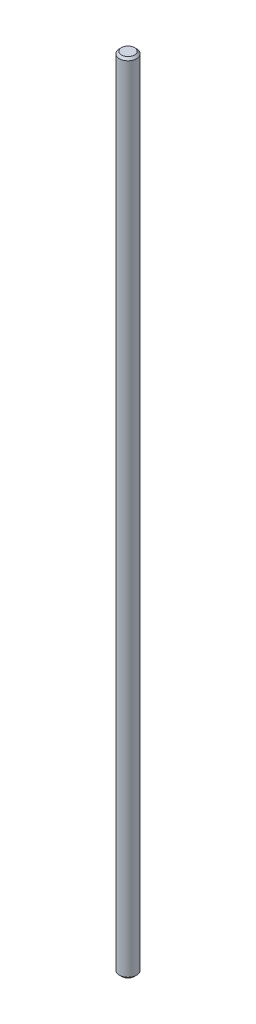
SolidWorks part; units mm, degrees
material "Plain Carbon Steel"
ref_plane "Front Plane" through (0, 0, 0) normal (0, 0, 1) x (1, 0, 0)
ref_plane "Top Plane" through (0, 0, 0) normal (0, 1, 0) x (1, 0, 0)
ref_plane "Right Plane" through (0, 0, 0) normal (1, 0, 0) x (0, 0, -1)
sketch "Sketch1" plane through (0, 0, 0) normal (0, 1, 0) x (1, 0, 0)
  circle A0 centre (0, 0) radius 4
  dimension "D1" = 8
extrude "Boss-Extrude1" add sketch "Sketch1" along normal blind 370
chamfer "Chamfer1" distance 1 angle 45 2 edges at (0, 0, 4) (0, 370, 4)
